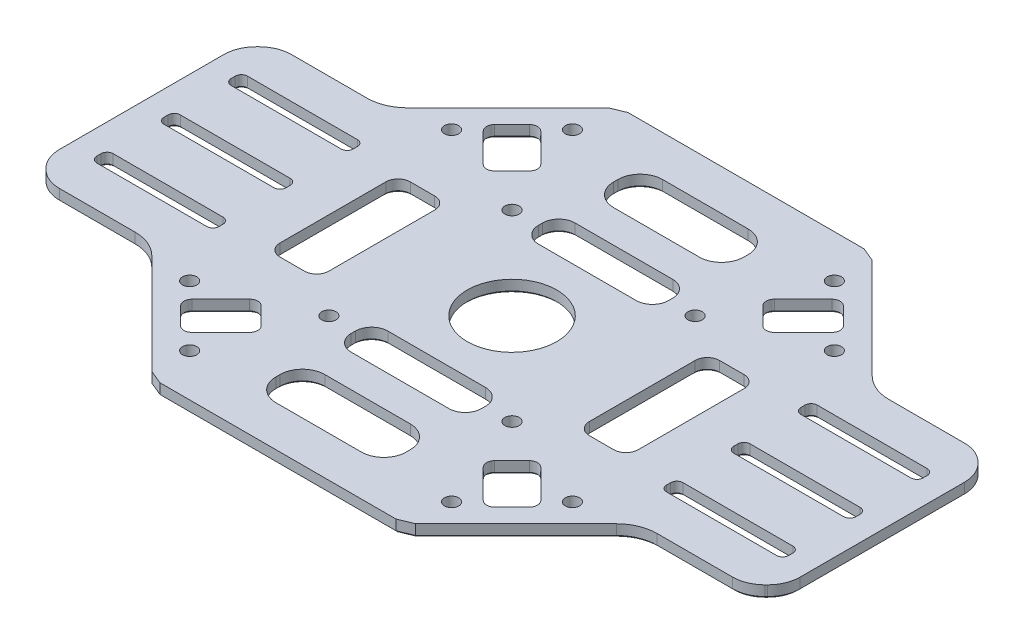
SolidWorks part; units mm, degrees
ref_plane "Спереди" through (0, 0, 0) normal (0, 0, 1) x (1, 0, 0)
ref_plane "Сверху" through (0, 0, 0) normal (0, 1, 0) x (1, 0, 0)
ref_plane "Справа" through (0, 0, 0) normal (1, 0, 0) x (0, 0, -1)
sketch "Эскиз1" plane through (0, 0, 0) normal (0, 1, 0) x (1, 0, 0)
  line L0 (-47.2118, 0) -> (134.7882, 0) construction
  line L1 (43.7882, -85.4485) -> (43.7882, 85.4485) construction
  line L2 (74.6039, 30.8143) -> (88.0389, 44.2493) construction
  line L3 (-47.2118, -20.1863) -> (-47.2118, 20.1863)
  line L4 (43.7882, 0) -> (74.6039, 30.8143) construction
  line L5 (59.7882, 23.5) -> (59.7882, 22.5)
  line L6 (-44.8686, 25.8431) -> (-44.5549, 26.1569)
  line L7 (72.7882, 57.5) -> (76.2024, 56.0858)
  line L8 (100.8593, 31.4289) -> (76.2024, 56.0858)
  line L9 (72.4825, 32.9356) -> (76.7252, 28.693)
  line L10 (86.6247, 35.7641) -> (79.5536, 28.693)
  line L11 (79.5536, 42.8351) -> (72.4825, 35.7641)
  line L12 (-38.8981, 28.5) -> (-20.3539, 28.5)
  line L13 (84.5034, 40.7138) -> (86.6247, 38.5925)
  line L14 (71.7882, 57.5) -> (15.7882, 57.5)
  line L15 (59.7882, 42) -> (59.7882, 41)
  line L16 (15.7882, 57.5) -> (14.7882, 57.5)
  line L17 (84.5034, 40.7138) -> (82.382, 42.8351)
  line L18 (75.7882, -13) -> (75.7882, 13)
  line L19 (-39.7118, 2) -> (-12.7118, 2)
  line L20 (-41.2118, 0.5) -> (-41.2118, -0.5)
  line L21 (84.7882, 16) -> (78.7882, 16)
  line L22 (-11.2118, 0.5) -> (-11.2118, -0.5)
  line L23 (87.7882, -13) -> (87.7882, 13)
  line L24 (100.2882, 18.5) -> (127.2882, 18.5)
  line L25 (127.2882, 14.5) -> (100.2882, 14.5)
  line L26 (128.7882, 17) -> (128.7882, 16)
  line L27 (98.7882, 16) -> (98.7882, 17)
  line L28 (98.7882, 0.5) -> (98.7882, -0.5)
  line L29 (128.7882, 0.5) -> (128.7882, -0.5)
  line L30 (127.2882, 2) -> (100.2882, 2)
  line L31 (71.7882, 57.5) -> (72.7882, 57.5)
  line L32 (126.4745, 28.5) -> (107.9304, 28.5)
  line L33 (132.4451, 25.8431) -> (132.1314, 26.1569)
  line L34 (134.7882, -20.1863) -> (134.7882, 20.1863)
  line L35 (12.9726, -30.8143) -> (-0.4624, -44.2493) construction
  line L36 (43.7882, 0) -> (12.9726, -30.8143) construction
  line L37 (43.7882, 0) -> (74.6039, -30.8143) construction
  line L38 (74.6039, -30.8143) -> (88.0389, -44.2493) construction
  line L39 (31.7882, -18.5) -> (55.7882, -18.5)
  line L40 (27.7882, -23.5) -> (27.7882, -22.5)
  line L41 (31.7882, -27.5) -> (55.7882, -27.5)
  line L42 (14.7882, -57.5) -> (11.374, -56.0858)
  line L43 (-13.2828, -31.4289) -> (11.374, -56.0858)
  line L44 (15.0939, -32.9356) -> (10.8513, -28.693)
  line L45 (0.9518, -35.7641) -> (8.0229, -28.693)
  line L46 (8.0229, -42.8351) -> (15.0939, -35.7641)
  line L47 (3.0731, -40.7138) -> (0.9518, -38.5925)
  line L48 (33.2882, -35.5) -> (54.2882, -35.5)
  line L49 (27.7882, -42) -> (27.7882, -41)
  line L50 (-11.2118, 16) -> (-11.2118, 17)
  line L51 (-41.2118, 17) -> (-41.2118, 16)
  line L52 (-39.7118, 14.5) -> (-12.7118, 14.5)
  line L53 (-12.7118, 18.5) -> (-39.7118, 18.5)
  line L54 (54.2882, -47.5) -> (33.2882, -47.5)
  line L55 (3.0731, -40.7138) -> (5.1944, -42.8351)
  line L56 (2.7882, -16) -> (8.7882, -16)
  line L57 (-12.7118, -18.5) -> (-39.7118, -18.5)
  line L58 (-39.7118, -14.5) -> (-12.7118, -14.5)
  line L59 (-41.2118, -17) -> (-41.2118, -16)
  line L60 (-11.2118, -16) -> (-11.2118, -17)
  line L61 (-0.2118, -13) -> (-0.2118, 13)
  line L62 (2.7882, 16) -> (8.7882, 16)
  line L63 (11.7882, -13) -> (11.7882, 13)
  line L64 (132.4451, -25.8431) -> (132.1314, -26.1569)
  line L65 (126.4745, -28.5) -> (107.9304, -28.5)
  line L66 (71.7882, -57.5) -> (72.7882, -57.5)
  line L67 (127.2882, -2) -> (100.2882, -2)
  line L68 (98.7882, -16) -> (98.7882, -17)
  line L69 (128.7882, -17) -> (128.7882, -16)
  line L70 (127.2882, -14.5) -> (100.2882, -14.5)
  line L71 (100.2882, -18.5) -> (127.2882, -18.5)
  line L72 (84.7882, -16) -> (78.7882, -16)
  line L73 (-39.7118, -2) -> (-12.7118, -2)
  line L74 (3.0731, 40.7138) -> (5.1944, 42.8351)
  line L75 (84.5034, -40.7138) -> (82.382, -42.8351)
  line L76 (54.2882, 47.5) -> (33.2882, 47.5)
  line L77 (27.7882, 42) -> (27.7882, 41)
  line L78 (33.2882, 35.5) -> (54.2882, 35.5)
  line L79 (15.7882, -57.5) -> (14.7882, -57.5)
  line L80 (3.0731, 40.7138) -> (0.9518, 38.5925)
  line L81 (8.0229, 42.8351) -> (15.0939, 35.7641)
  line L82 (0.9518, 35.7641) -> (8.0229, 28.693)
  line L83 (15.0939, 32.9356) -> (10.8513, 28.693)
  line L84 (59.7882, -42) -> (59.7882, -41)
  line L85 (71.7882, -57.5) -> (15.7882, -57.5)
  line L86 (84.5034, -40.7138) -> (86.6247, -38.5925)
  line L87 (-38.8981, -28.5) -> (-20.3539, -28.5)
  line L88 (79.5536, -42.8351) -> (72.4825, -35.7641)
  line L89 (86.6247, -35.7641) -> (79.5536, -28.693)
  line L90 (72.4825, -32.9356) -> (76.7252, -28.693)
  line L91 (100.8593, -31.4289) -> (76.2024, -56.0858)
  line L92 (72.7882, -57.5) -> (76.2024, -56.0858)
  line L93 (-44.8686, -25.8431) -> (-44.5549, -26.1569)
  line L94 (59.7882, -23.5) -> (59.7882, -22.5)
  line L102 (-13.2828, 31.4289) -> (11.374, 56.0858)
  line L103 (43.7882, 0) -> (12.9726, 30.8143) construction
  line L104 (12.9726, 30.8143) -> (-0.4624, 44.2493) construction
  line L107 (14.7882, 57.5) -> (11.374, 56.0858)
  line L110 (31.7882, 27.5) -> (55.7882, 27.5)
  line L111 (27.7882, 23.5) -> (27.7882, 22.5)
  line L112 (31.7882, 18.5) -> (55.7882, 18.5)
  circle A0 centre (43.7882, 0) radius 11
  arc A1 (-11.2118, 0.5) -> (-12.7118, 2) centre (-12.7118, 0.5) ccw
  arc A2 (-41.2118, 0.5) -> (-39.7118, 2) centre (-39.7118, 0.5) cw
  arc A3 (-44.8686, 25.8431) -> (-47.2118, 20.1863) centre (-39.2118, 20.1863) ccw
  arc A4 (-44.5549, 26.1569) -> (-38.8981, 28.5) centre (-38.8981, 20.5) cw
  arc A5 (59.7882, 42) -> (54.2882, 47.5) centre (54.2882, 42) ccw
  arc A6 (59.7882, 41) -> (54.2882, 35.5) centre (54.2882, 41) cw
  arc A7 (59.7882, 23.5) -> (55.7882, 27.5) centre (55.7882, 23.5) ccw
  arc A8 (59.7882, 22.5) -> (55.7882, 18.5) centre (55.7882, 22.5) cw
  arc A9 (107.9304, 28.5) -> (100.8593, 31.4289) centre (107.9304, 38.5) cw
  arc A10 (87.7882, 13) -> (84.7882, 16) centre (84.7882, 13) ccw
  arc A11 (78.7882, 16) -> (75.7882, 13) centre (78.7882, 13) ccw
  arc A12 (82.382, 42.8351) -> (79.5536, 42.8351) centre (80.9678, 41.4209) ccw
  arc A13 (72.4825, 35.7641) -> (72.4825, 32.9356) centre (73.8968, 34.3498) ccw
  arc A14 (79.5536, 28.693) -> (76.7252, 28.693) centre (78.1394, 30.1072) cw
  arc A15 (86.6247, 38.5925) -> (86.6247, 35.7641) centre (85.2105, 37.1783) cw
  arc A16 (-41.2118, 17) -> (-39.7118, 18.5) centre (-39.7118, 17) cw
  arc A17 (-41.2118, 16) -> (-39.7118, 14.5) centre (-39.7118, 16) ccw
  arc A18 (-11.2118, 16) -> (-12.7118, 14.5) centre (-12.7118, 16) cw
  arc A19 (-11.2118, 17) -> (-12.7118, 18.5) centre (-12.7118, 17) ccw
  arc A20 (98.7882, 17) -> (100.2882, 18.5) centre (100.2882, 17) cw
  arc A21 (98.7882, 16) -> (100.2882, 14.5) centre (100.2882, 16) ccw
  arc A22 (128.7882, 16) -> (127.2882, 14.5) centre (127.2882, 16) cw
  arc A23 (128.7882, 17) -> (127.2882, 18.5) centre (127.2882, 17) ccw
  arc A24 (132.1314, 26.1569) -> (126.4745, 28.5) centre (126.4745, 20.5) ccw
  arc A25 (132.4451, 25.8431) -> (134.7882, 20.1863) centre (126.7882, 20.1863) cw
  arc A26 (128.7882, 0.5) -> (127.2882, 2) centre (127.2882, 0.5) ccw
  arc A27 (98.7882, 0.5) -> (100.2882, 2) centre (100.2882, 0.5) cw
  arc A28 (0.9518, 38.5925) -> (0.9518, 35.7641) centre (2.366, 37.1783) ccw
  arc A29 (8.0229, 28.693) -> (10.8513, 28.693) centre (9.4371, 30.1072) ccw
  arc A30 (15.0939, 35.7641) -> (15.0939, 32.9356) centre (13.6797, 34.3498) cw
  arc A31 (5.1944, 42.8351) -> (8.0229, 42.8351) centre (6.6086, 41.4209) cw
  arc A32 (27.7882, -42) -> (33.2882, -47.5) centre (33.2882, -42) ccw
  arc A33 (27.7882, -41) -> (33.2882, -35.5) centre (33.2882, -41) cw
  arc A34 (27.7882, -23.5) -> (31.7882, -27.5) centre (31.7882, -23.5) ccw
  arc A35 (27.7882, -22.5) -> (31.7882, -18.5) centre (31.7882, -22.5) cw
  arc A36 (-20.3539, -28.5) -> (-13.2828, -31.4289) centre (-20.3539, -38.5) cw
  arc A37 (-0.2118, -13) -> (2.7882, -16) centre (2.7882, -13) ccw
  arc A38 (8.7882, -16) -> (11.7882, -13) centre (8.7882, -13) ccw
  arc A39 (5.1944, -42.8351) -> (8.0229, -42.8351) centre (6.6086, -41.4209) ccw
  arc A40 (15.0939, -35.7641) -> (15.0939, -32.9356) centre (13.6797, -34.3498) ccw
  arc A41 (8.0229, -28.693) -> (10.8513, -28.693) centre (9.4371, -30.1072) cw
  arc A42 (0.9518, -38.5925) -> (0.9518, -35.7641) centre (2.366, -37.1783) cw
  arc A43 (98.7882, -0.5) -> (100.2882, -2) centre (100.2882, -0.5) ccw
  arc A44 (128.7882, -0.5) -> (127.2882, -2) centre (127.2882, -0.5) cw
  arc A45 (132.4451, -25.8431) -> (134.7882, -20.1863) centre (126.7882, -20.1863) ccw
  arc A46 (132.1314, -26.1569) -> (126.4745, -28.5) centre (126.4745, -20.5) cw
  arc A47 (128.7882, -17) -> (127.2882, -18.5) centre (127.2882, -17) cw
  arc A48 (128.7882, -16) -> (127.2882, -14.5) centre (127.2882, -16) ccw
  arc A49 (98.7882, -16) -> (100.2882, -14.5) centre (100.2882, -16) cw
  arc A50 (8.7882, 16) -> (11.7882, 13) centre (8.7882, 13) cw
  arc A51 (-0.2118, 13) -> (2.7882, 16) centre (2.7882, 13) cw
  arc A52 (98.7882, -17) -> (100.2882, -18.5) centre (100.2882, -17) ccw
  arc A53 (-11.2118, -17) -> (-12.7118, -18.5) centre (-12.7118, -17) cw
  arc A54 (-11.2118, -16) -> (-12.7118, -14.5) centre (-12.7118, -16) ccw
  arc A55 (-41.2118, -16) -> (-39.7118, -14.5) centre (-39.7118, -16) cw
  arc A56 (-41.2118, -17) -> (-39.7118, -18.5) centre (-39.7118, -17) ccw
  arc A57 (86.6247, -38.5925) -> (86.6247, -35.7641) centre (85.2105, -37.1783) ccw
  arc A58 (79.5536, -28.693) -> (76.7252, -28.693) centre (78.1394, -30.1072) ccw
  arc A59 (72.4825, -35.7641) -> (72.4825, -32.9356) centre (73.8968, -34.3498) cw
  arc A60 (82.382, -42.8351) -> (79.5536, -42.8351) centre (80.9678, -41.4209) cw
  arc A61 (78.7882, -16) -> (75.7882, -13) centre (78.7882, -13) cw
  arc A62 (87.7882, -13) -> (84.7882, -16) centre (84.7882, -13) cw
  arc A63 (-20.3539, 28.5) -> (-13.2828, 31.4289) centre (-20.3539, 38.5) ccw
  arc A64 (107.9304, -28.5) -> (100.8593, -31.4289) centre (107.9304, -38.5) ccw
  arc A65 (59.7882, -22.5) -> (55.7882, -18.5) centre (55.7882, -22.5) ccw
  arc A66 (27.7882, 22.5) -> (31.7882, 18.5) centre (31.7882, 22.5) ccw
  arc A67 (27.7882, 23.5) -> (31.7882, 27.5) centre (31.7882, 23.5) cw
  arc A68 (27.7882, 41) -> (33.2882, 35.5) centre (33.2882, 41) ccw
  arc A69 (27.7882, 42) -> (33.2882, 47.5) centre (33.2882, 42) cw
  arc A70 (59.7882, -23.5) -> (55.7882, -27.5) centre (55.7882, -23.5) cw
  arc A71 (59.7882, -41) -> (54.2882, -35.5) centre (54.2882, -41) ccw
  arc A72 (59.7882, -42) -> (54.2882, -47.5) centre (54.2882, -42) cw
  arc A73 (-44.5549, -26.1569) -> (-38.8981, -28.5) centre (-38.8981, -20.5) ccw
  arc A74 (-44.8686, -25.8431) -> (-47.2118, -20.1863) centre (-39.2118, -20.1863) cw
  arc A75 (-41.2118, -0.5) -> (-39.7118, -2) centre (-39.7118, -0.5) ccw
  arc A76 (-11.2118, -0.5) -> (-12.7118, -2) centre (-12.7118, -0.5) cw
  point P5 (-47.2118, 23.5)
  point P8 (-47.2118, 28.5)
  point P11 (103.7882, 28.5)
  point P13 (-42.2118, 28.5)
  point P14 (43.7882, 18.5)
  point P16 (43.7882, 47.5)
  point P28 (-41.2118, 0)
  point P36 (12.7882, 57.5)
  point P65 (-0.2118, 0)
  point P76 (75.7882, 0)
  point P105 (43.7882, 27.5)
  point P109 (43.7882, 35.5)
  point P110 (-11.2118, 0)
  point P111 (87.7882, 0)
  point P112 (98.7882, 0)
  point P114 (43.7882, 57.5)
  point P115 (87.7882, 16)
  point P116 (75.7882, 16)
  point P117 (80.9678, 44.2493)
  point P118 (71.0683, 34.3498)
  point P119 (78.1394, 27.2788)
  point P120 (88.0389, 37.1783)
  point P121 (98.7882, 18.5)
  point P122 (98.7882, 14.5)
  point P123 (128.7882, 14.5)
  point P124 (128.7882, 18.5)
  point P125 (74.7882, 57.5)
  point P126 (129.7882, 28.5)
  point P127 (134.7882, 28.5)
  point P128 (134.7882, 23.5)
  point P148 (-41.2118, 18.5)
  point P151 (-41.2118, 14.5)
  point P154 (-11.2118, 14.5)
  point P157 (-11.2118, 18.5)
  point P184 (-0.4624, 37.1783)
  point P187 (9.4371, 27.2788)
  point P190 (16.5081, 34.3498)
  point P193 (6.6086, 44.2493)
  point P250 (11.7882, 16)
  point P253 (-0.2118, 16)
  point P280 (11.7882, 0)
  point P282 (128.7882, 0)
  point P285 (-16.2118, -28.5)
  point P286 (-0.2118, -16)
  point P287 (11.7882, -16)
  point P288 (6.6086, -44.2493)
  point P289 (16.5081, -34.3498)
  point P290 (9.4371, -27.2788)
  point P293 (-16.2118, 28.5)
  point P294 (-0.4624, -37.1783)
  point P295 (-11.2118, -18.5)
  point P296 (-11.2118, -14.5)
  point P297 (-41.2118, -14.5)
  point P298 (-41.2118, -18.5)
  point P301 (134.7882, -23.5)
  point P302 (134.7882, -28.5)
  point P304 (129.7882, -28.5)
  point P307 (74.7882, -57.5)
  point P317 (128.7882, -18.5)
  point P318 (128.7882, -14.5)
  point P319 (98.7882, -14.5)
  point P320 (98.7882, -18.5)
  point P321 (88.0389, -37.1783)
  point P322 (78.1394, -27.2788)
  point P323 (71.0683, -34.3498)
  point P324 (80.9678, -44.2493)
  point P325 (75.7882, -16)
  point P326 (87.7882, -16)
  point P327 (43.7882, -57.5)
  point P328 (43.7882, -35.5)
  point P329 (43.7882, -27.5)
  point P330 (12.7882, -57.5)
  point P331 (43.7882, -47.5)
  point P332 (43.7882, -18.5)
  point P333 (-42.2118, -28.5)
  point P334 (103.7882, -28.5)
  point P335 (-47.2118, -28.5)
  point P336 (-47.2118, -23.5)
  dimension "D19" = 2
  dimension "D21" = 2
  dimension "D32" = 4
  dimension "D36" = 5.5
  dimension "D9" = 22
  dimension "D38" = 1.5
  dimension "D4" = 8
  dimension "D2" = 5
  dimension "D3" = 14
  dimension "D6" = 31
  dimension "D10" = 57.5
  dimension "D31" = 9
  dimension "D35" = 8
  dimension "D37" = 47
extrude "Бобышка-Вытянуть1" add sketch "Эскиз1" along normal blind 3
sketch "Эскиз2" plane through (0, 3, 0) normal (0, 1, 0) x (1, 0, 0)
  line L14 (4.1902, 39.598) -> (11.6149, 47.0226) construction
  line L15 (4.1902, 39.598) -> (-3.2344, 32.1734) construction
  circle A0 centre (11.6149, 47.0226) radius 1.75
  circle A1 centre (-3.2344, 32.1734) radius 1.75
  circle A2 centre (75.9616, 47.0226) radius 1.75
  circle A3 centre (90.8108, 32.1734) radius 1.75
  circle A4 centre (90.8108, -32.1734) radius 1.75
  circle A5 centre (75.9616, -47.0226) radius 1.75
  circle A6 centre (11.6149, -47.0226) radius 1.75
  circle A7 centre (-3.2344, -32.1734) radius 1.75
  dimension "D1" = 10.5
  dimension "D3" = 3.5
  dimension "D4" = 10.5
extrude "Вырез-Вытянуть1" cut sketch "Эскиз2" against normal blind 10
chamfer "Chaflán1" distance 0.5 angle 45 169 edges at (43.7882, 0, 11) (113.7882, 0, 18.5) (99.2276, 0, 18.0607) (98.7882, 0, 16.5) (99.2276, 0, 14.9393) (113.7882, 0, 14.5) (128.3489, 0, 14.9393) (128.7882, 0, 16.5) (128.3489, 0, 18.0607) (-0.2118, 0, 0) (0.6669, 0, -15.1213) (5.7882, 0, -16) (10.9096, 0, -15.1213) (11.7882, 0, 0) (10.9096, 0, 15.1213) (5.7882, 0, 16) (0.6669, 0, 15.1213) (27.7882, 0, 23) (28.9598, 0, 19.6716) (43.7882, 0, 18.5) (58.6167, 0, 19.6716) (59.7882, 0, 23) (58.6167, 0, 26.3284) (43.7882, 0, 27.5) (28.9598, 0, 26.3284) (128.7882, 0, 0) (128.3489, 0, 1.5607) (113.7882, 0, 2) (99.2276, 0, 1.5607) (98.7882, 0, 0) (99.2276, 0, -1.5607) (113.7882, 0, -2) (128.3489, 0, -1.5607) (84.5034, 0, 40.7138) (80.9678, 0, 43.4209) (76.0181, 0, 39.2996) (71.8968, 0, 34.3498) (74.6039, 0, 30.8143) (78.1394, 0, 28.1072) (83.0891, 0, 32.2285) (87.2105, 0, 37.1783) (84.5034, 0, -40.7138) (87.2105, 0, -37.1783) (83.0891, 0, -32.2285) (78.1394, 0, -28.1072) (74.6039, 0, -30.8143) (71.8968, 0, -34.3498) (76.0181, 0, -39.2996) (80.9678, 0, -43.4209) (59.7882, 0, -23) (58.6167, 0, -19.6716) (43.7882, 0, -18.5) (28.9598, 0, -19.6716) (27.7882, 0, -23) (28.9598, 0, -26.3284) (43.7882, 0, -27.5) (58.6167, 0, -26.3284) (59.7882, 0, -41.5) (58.1773, 0, -37.1109) (43.7882, 0, -35.5) (29.3991, 0, -37.1109) (27.7882, 0, -41.5) (29.3991, 0, -45.8891) (43.7882, 0, -47.5) (58.1773, 0, -45.8891) (-47.2118, 0, 0) (-46.6028, 0, 23.2478) (-44.7118, 0, 26) (-41.9595, 0, 27.891) (-29.626, 0, 28.5) (-16.5271, 0, 29.2612) (-0.9544, 0, 43.7574) (13.0811, 0, 56.7929) (43.7882, 0, 57.5) (74.4953, 0, 56.7929) (88.5309, 0, 43.7574) (104.1035, 0, 29.2612) (117.2024, 0, 28.5) (129.536, 0, 27.891) (132.2882, 0, 26) (134.1793, 0, 23.2478) (134.7882, 0, 0) (134.1793, 0, -23.2478) (132.2882, 0, -26) (129.536, 0, -27.891) (117.2024, 0, -28.5) (104.1035, 0, -29.2612) (88.5309, 0, -43.7574) (74.4953, 0, -56.7929) (43.7882, 0, -57.5) (13.0811, 0, -56.7929) (-0.9544, 0, -43.7574) (-16.5271, 0, -29.2612) (-29.626, 0, -28.5) (-41.9595, 0, -27.891) (-44.7118, 0, -26) (-46.6028, 0, -23.2478) (-11.2118, 0, 0) (-11.6511, 0, 1.5607) (-26.2118, 0, 2) (-40.7724, 0, 1.5607) (-41.2118, 0, 0) (-40.7724, 0, -1.5607) (-26.2118, 0, -2) (-11.6511, 0, -1.5607) (87.7882, 0, 0) (86.9096, 0, 15.1213) (81.7882, 0, 16) (76.6669, 0, 15.1213) (75.7882, 0, 0) (76.6669, 0, -15.1213) (81.7882, 0, -16) (86.9096, 0, -15.1213) (113.7882, 0, -18.5) (128.3489, 0, -18.0607) (128.7882, 0, -16.5) (128.3489, 0, -14.9393) (113.7882, 0, -14.5) (99.2276, 0, -14.9393) (98.7882, 0, -16.5) (99.2276, 0, -18.0607) (3.0731, 0, -40.7138) (6.6086, 0, -43.4209) (11.5584, 0, -39.2996) (15.6797, 0, -34.3498) (12.9726, 0, -30.8143) (9.4371, 0, -28.1072) (4.4873, 0, -32.2285) (0.366, 0, -37.1783) (27.7882, 0, 41.5) (29.3991, 0, 37.1109) (43.7882, 0, 35.5) (58.1773, 0, 37.1109) (59.7882, 0, 41.5) (58.1773, 0, 45.8891) (43.7882, 0, 47.5) (29.3991, 0, 45.8891) (-26.2118, 0, -18.5) (-11.6511, 0, -18.0607) (-11.2118, 0, -16.5) (-11.6511, 0, -14.9393) (-26.2118, 0, -14.5) (-40.7724, 0, -14.9393) (-41.2118, 0, -16.5) (-40.7724, 0, -18.0607) (3.0731, 0, 40.7138) (0.366, 0, 37.1783) (4.4873, 0, 32.2285) (9.4371, 0, 28.1072) (12.9726, 0, 30.8143) (15.6797, 0, 34.3498) (11.5584, 0, 39.2996) (6.6086, 0, 43.4209) (-26.2118, 0, 18.5) (-40.7724, 0, 18.0607) (-41.2118, 0, 16.5) (-40.7724, 0, 14.9393) (-26.2118, 0, 14.5) (-11.6511, 0, 14.9393) (-11.2118, 0, 16.5) (-11.6511, 0, 18.0607) (11.6149, 0, -45.2726) (-3.2344, 0, -30.4234) (75.9616, 0, -45.2726) (90.8108, 0, -30.4234) (90.8108, 0, 33.9234) (75.9616, 0, 48.7726) (11.6149, 0, 48.7726) (-3.2344, 0, 33.9234)
sketch "Croquis1" plane through (0, 3, 0) normal (0, 1, 0) x (1, 0, 0)
  line L0 (43.7882, 0) -> (43.7882, -14.2245) construction
  line L1 (43.7882, 0) -> (62.8104, 0) construction
  circle A0 centre (21.2882, 22.5) radius 1.75
  circle A1 centre (43.7882, 0) radius 11 construction
  circle A2 centre (66.2882, 22.5) radius 1.75
  circle A3 centre (66.2882, -22.5) radius 1.75
  circle A4 centre (21.2882, -22.5) radius 1.75
  dimension "D1" = 3.5
  dimension "D2" = 22.5
  dimension "D3" = 22.5
extrude "Cortar-Extruir1" cut sketch "Croquis1" against normal up to next
chamfer "Chaflán2" distance 0.5 angle 45 4 edges at (66.2882, 0, -20.75) (66.2882, 0, 24.25) (21.2882, 0, 24.25) (21.2882, 0, -20.75)
equation "\"D3@Croquis1\"=\"D2@Croquis1\""
